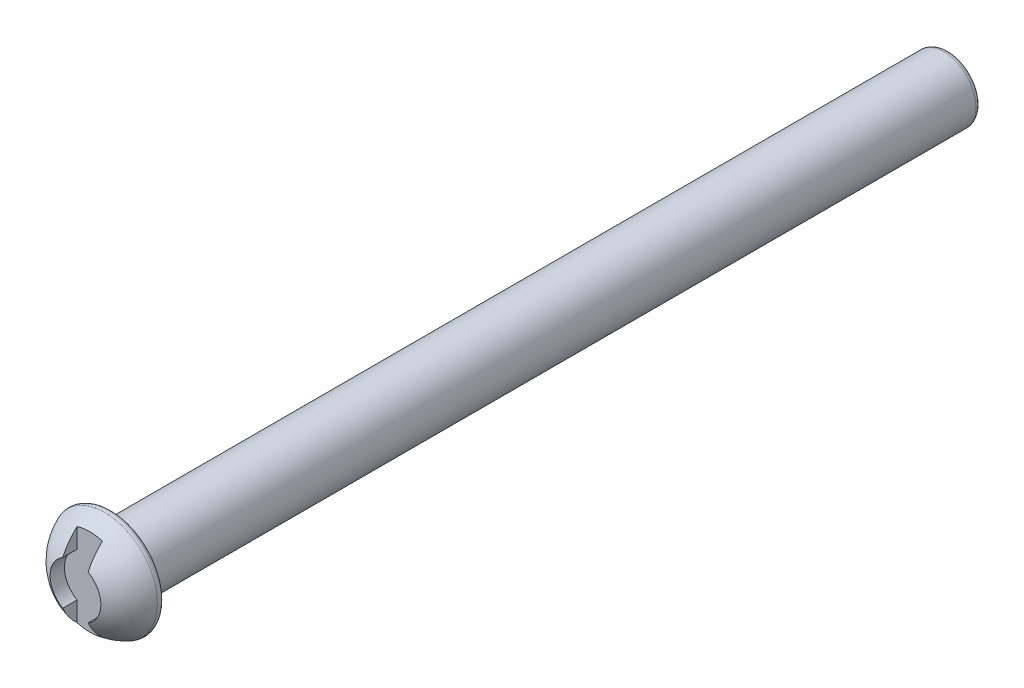
SolidWorks part; units mm, degrees
ref_plane "Front Plane" through (0, 0, 0) normal (0, 0, 1) x (1, 0, 0)
ref_plane "Top Plane" through (0, 0, 0) normal (0, 1, 0) x (1, 0, 0)
ref_plane "Right Plane" through (0, 0, 0) normal (1, 0, 0) x (0, 0, -1)
sketch "Sketch1" plane through (0, 0, 0) normal (1, 0, 0) x (0, 0, -1)
  line L0 (0, 0) -> (26, 0)
  line L1 (26, 0) -> (26, 0.95)
  line L2 (26, 0.95) -> (1.25, 0.95)
  line L3 (1.25, 0.95) -> (1.25, 1.625)
  arc A1 (1.25, 1.625) -> (0, 0) centre (1.6812, 0) ccw
  dimension "D1" = 26
  dimension "D2" = 0.95
  dimension "D3" = 1.625
  dimension "D4" = 1.25
revolve "Revolve1" add sketch "Sketch1" angle 360 about L0
sketch "Sketch2" plane through (0, 0, 0) normal (0, 0, 1) x (1, 0, 0)
  line L0 (0.375, -0.6495) -> (0.375, -1.9103)
  line L1 (-0.375, 1.9103) -> (0.375, 1.9103)
  line L2 (-0.375, 1.9103) -> (-0.375, 0.6495)
  line L3 (-0.375, -1.9103) -> (0.375, -1.9103)
  line L4 (0.375, 1.9103) -> (0.375, 0.6495)
  line L5 (-0.375, 1.9103) -> (0.375, -1.9103) construction
  line L6 (-0.375, -1.9103) -> (0.375, 1.9103) construction
  line L7 (-0.375, -0.6495) -> (-0.375, -1.9103)
  arc A0 (-0.375, 0.6495) -> (-0.375, -0.6495) centre (0, 0) ccw
  arc A1 (0.375, -0.6495) -> (0.375, 0.6495) centre (0, 0) ccw
  point P0 (0, 0)
  dimension "D2" = 1.5
  dimension "D1" = 0.75
extrude "Cut-Extrude1" cut sketch "Sketch2" against normal blind 0.6
fillet "Fillet1" radius 0.15 2 edges at (0.95, 0, -26) (1.625, 0, -1.25)
